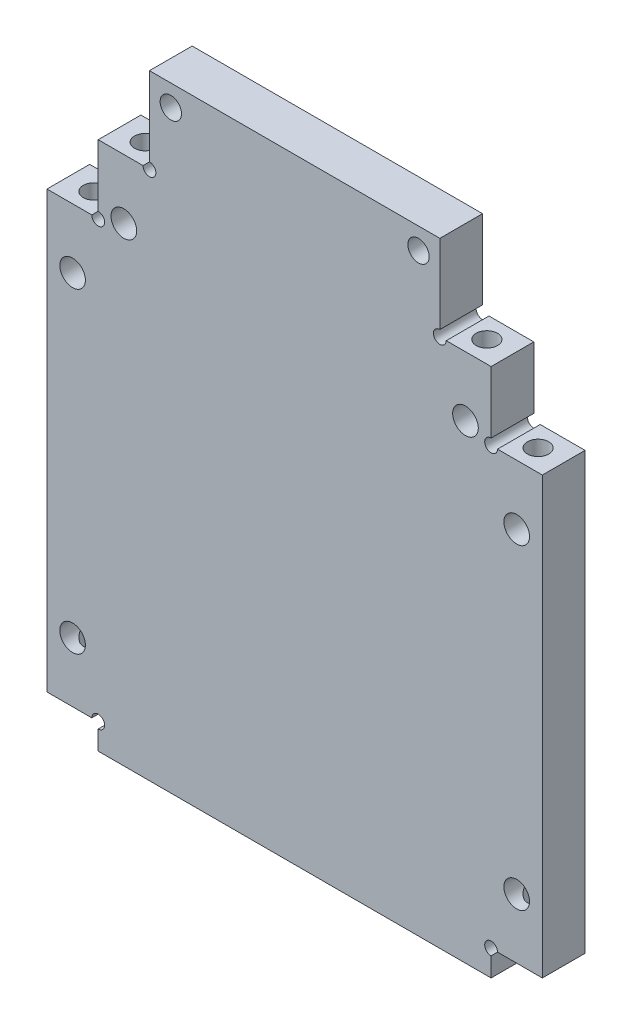
SolidWorks part; units mm, degrees
material "5052-O"
ref_plane "正面" through (0, 0, 0) normal (0, 0, 1) x (1, 0, 0)
ref_plane "平面" through (0, 0, 0) normal (0, 1, 0) x (1, 0, 0)
ref_plane "右側面" through (0, 0, 0) normal (1, 0, 0) x (0, 0, -1)
sketch "ｽｹｯﾁ1" plane through (0, 0, 0) normal (0, 0, 1) x (1, 0, 0)
  line L0 (-29, 51) -> (-29, 0)
  line L1 (-29, 0) -> (-23, 0)
  line L2 (29, 0) -> (29, 51)
  line L3 (-29, 51) -> (-23, 51)
  line L4 (-23, 51) -> (-23, 59)
  line L5 (-23, 59) -> (-17, 59)
  line L6 (-17, 59) -> (-17, 69)
  line L7 (-17, 69) -> (17, 69)
  line L8 (17, 69) -> (17, 59)
  line L9 (17, 59) -> (23, 59)
  line L10 (23, 59) -> (23, 51)
  line L11 (23, 51) -> (29, 51)
  line L12 (-23, 0) -> (-23, -3)
  line L13 (-23, -3) -> (23, -3)
  line L14 (23, -3) -> (23, 0)
  line L15 (23, 0) -> (29, 0)
  line L16 (0, 0) -> (0, -3) construction
  dimension "D1" = 58
  dimension "D2" = 51
  dimension "D3" = 6
  dimension "D4" = 8
  dimension "D5" = 10
  dimension "D6" = 3
extrude "ﾎﾞｽ - 押し出し1" add sketch "ｽｹｯﾁ1" along normal blind 5
sketch "ｽｹｯﾁ2" plane through (0, 59, 0) normal (0, 1, 0) x (1, 0, 0)
  line L0 (-23, -2.5) -> (-17, -2.5) construction
  line L1 (-23, -5) -> (-23, 0) construction
  line L2 (-17, -5) -> (-17, 0) construction
  line L4 (17, -5) -> (17, 0) construction
  line L5 (17, -2.5) -> (23, -2.5) construction
  line L6 (23, -5) -> (23, 0) construction
  circle A0 centre (-20, -2.5) radius 1.25
  circle A1 centre (20, -2.5) radius 1.25
  dimension "D1" = 2.5
extrude "ｶｯﾄ - 押し出し1" cut sketch "ｽｹｯﾁ2" against normal blind 7.5
sketch "ｽｹｯﾁ3" plane through (0, 51, 0) normal (0, 1, 0) x (1, 0, 0)
  line L0 (-29, -2.5) -> (-23, -2.5) construction
  line L1 (-29, -5) -> (-29, 0) construction
  line L2 (-23, -5) -> (-23, 0) construction
  line L4 (23, -5) -> (23, 0) construction
  line L5 (23, -2.5) -> (29, -2.5) construction
  line L6 (29, -5) -> (29, 0) construction
  circle A0 centre (-26, -2.5) radius 1.25
  circle A1 centre (26, -2.5) radius 1.25
  dimension "D1" = 2.5
extrude "ｶｯﾄ - 押し出し2" cut sketch "ｽｹｯﾁ3" against normal blind 7.5
ref_plane "平面1" through (0, 25.5, 0) normal (0, 1, 0) x (1, 0, 0)
mirror "ﾐﾗｰ1" about plane through (0, 25.5, 0) normal (0, 1, 0) of "ｶｯﾄ - 押し出し2"
sketch "ｽｹｯﾁ4" plane through (0, 0, 0) normal (0, 0, -1) x (-1, 0, 0)
  line L0 (-17, 66.5) -> (17, 66.5) construction
  line L1 (-17, 59) -> (-17, 69) construction
  line L2 (17, 69) -> (17, 59) construction
  line L3 (-17, 69) -> (17, 69) construction
  circle A0 centre (-14.5, 66.5) radius 1.25
  circle A1 centre (14.5, 66.5) radius 1.25
  dimension "D2" = 2.5
  dimension "D3" = 2.5
  dimension "D4" = 2.5
  dimension "D1" = 2.5
extrude "ｶｯﾄ - 押し出し3" cut sketch "ｽｹｯﾁ4" against normal through all
sketch "ｽｹｯﾁ5" plane through (0, 0, 0) normal (0, 0, -1) x (-1, 0, 0)
  circle A0 centre (-17, 59) radius 0.75
  circle A1 centre (-23, 51) radius 0.75
  circle A2 centre (-23, 0) radius 0.75
  circle A3 centre (17, 59) radius 0.75
  circle A4 centre (23, 51) radius 0.75
  circle A5 centre (23, 0) radius 0.75
  dimension "D1" = 1.5
extrude "ｶｯﾄ - 押し出し4" cut sketch "ｽｹｯﾁ5" against normal through all
sketch "ｽｹｯﾁ6" plane through (0, 0, 0) normal (0, 0, -1) x (-1, 0, 0)
  line L0 (0, -3) -> (0, 69) construction
  line L1 (23, -3) -> (-23, -3) construction
  line L2 (-17, 69) -> (17, 69) construction
  line L3 (-26, 0) -> (-26, 51) construction
  line L4 (-23.75, 0) -> (-29, 0) construction
  line L5 (-29, 51) -> (-23.75, 51) construction
  line L6 (-20, 59) -> (-20, -3) construction
  line L7 (-23, 59) -> (-17.75, 59) construction
  line L8 (-29, 0) -> (-29, 51) construction
  line L10 (-23, 51.75) -> (-23, 59) construction
  line L11 (-26, 8.5) -> (-26, 6.5) construction
  line L12 (-24.5, 8.5) -> (-24.5, 6.5)
  line L13 (-27.5, 8.5) -> (-27.5, 6.5)
  line L14 (-26, 42.5) -> (-26, 44.5) construction
  line L15 (-27.5, 42.5) -> (-27.5, 44.5)
  line L16 (-24.5, 42.5) -> (-24.5, 44.5)
  line L17 (-20, 50.5) -> (-20, 52.5) construction
  line L18 (-21.5, 50.5) -> (-21.5, 52.5)
  line L19 (-18.5, 50.5) -> (-18.5, 52.5)
  line L23 (26, 8.5) -> (26, 6.5) construction
  line L24 (24.5, 8.5) -> (24.5, 6.5)
  line L25 (27.5, 8.5) -> (27.5, 6.5)
  line L26 (26, 42.5) -> (26, 44.5) construction
  line L27 (27.5, 42.5) -> (27.5, 44.5)
  line L28 (24.5, 42.5) -> (24.5, 44.5)
  line L29 (20, 50.5) -> (20, 52.5) construction
  line L30 (21.5, 50.5) -> (21.5, 52.5)
  line L31 (18.5, 50.5) -> (18.5, 52.5)
  arc A0 (-24.5, 8.5) -> (-27.5, 8.5) centre (-26, 8.5) ccw
  arc A1 (-27.5, 6.5) -> (-24.5, 6.5) centre (-26, 6.5) ccw
  arc A2 (-27.5, 42.5) -> (-24.5, 42.5) centre (-26, 42.5) ccw
  arc A3 (-24.5, 44.5) -> (-27.5, 44.5) centre (-26, 44.5) ccw
  arc A4 (-21.5, 50.5) -> (-18.5, 50.5) centre (-20, 50.5) ccw
  arc A5 (-18.5, 52.5) -> (-21.5, 52.5) centre (-20, 52.5) ccw
  arc A8 (24.5, 8.5) -> (27.5, 8.5) centre (26, 8.5) cw
  arc A9 (27.5, 6.5) -> (24.5, 6.5) centre (26, 6.5) cw
  arc A10 (27.5, 42.5) -> (24.5, 42.5) centre (26, 42.5) cw
  arc A11 (24.5, 44.5) -> (27.5, 44.5) centre (26, 44.5) cw
  arc A12 (21.5, 50.5) -> (18.5, 50.5) centre (20, 50.5) cw
  arc A13 (18.5, 52.5) -> (21.5, 52.5) centre (20, 52.5) cw
  point P22 (-26, 7.5)
  point P28 (-26, 43.5)
  point P35 (-20, 51.5)
  point P51 (26, 7.5)
  point P58 (26, 43.5)
  point P65 (20, 51.5)
  dimension "D3" = 1.5
  dimension "D1" = 3
  dimension "D2" = 3
  dimension "D4" = 2
  dimension "D5" = 7.5
  dimension "D6" = 7.5
  dimension "D7" = 7.5
extrude "ｶｯﾄ - 押し出し5" [suppressed] cut sketch "ｽｹｯﾁ6" against normal through all
sketch "ｽｹｯﾁ7" plane through (0, 0, 5) normal (0, 0, 1) x (1, 0, 0)
  line L0 (-26, 51) -> (-26, 0) construction
  line L1 (-23.75, 51) -> (-29, 51) construction
  line L2 (-29, 0) -> (-23.75, 0) construction
  line L3 (-29, 51) -> (-29, 0) construction
  line L4 (-20, 59) -> (-20, -3) construction
  line L5 (-17.75, 59) -> (-23, 59) construction
  line L6 (-23, -3) -> (23, -3) construction
  line L7 (2.75, 25.5) -> (-2.75, 25.5) construction
  line L8 (0, 0) -> (0, 69) construction
  line L9 (17, 69) -> (-17, 69) construction
  line L10 (20, 59) -> (20, -3) construction
  line L11 (26, 51) -> (26, 0) construction
  circle A0 centre (-26, 44) radius 1.5
  circle A1 centre (-26, 7) radius 1.5
  circle A2 centre (-20, 52) radius 1.5
  circle A3 centre (20, 52) radius 1.5
  circle A4 centre (26, 7) radius 1.5
  circle A5 centre (26, 44) radius 1.5
  dimension "D3" = 7
  dimension "D4" = 3
  dimension "D5" = 7
  dimension "D1" = 3
  dimension "D2" = 9
extrude "ｶｯﾄ - 押し出し6" cut sketch "ｽｹｯﾁ7" against normal through all
